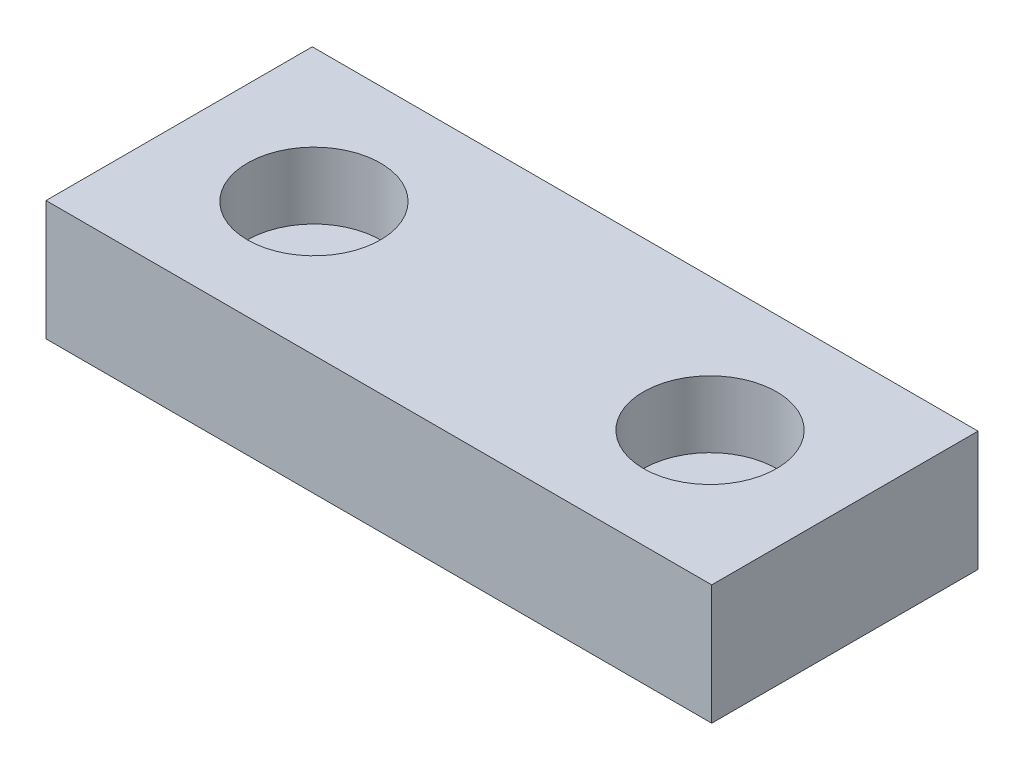
SolidWorks part; units mm, degrees
ref_plane "Front Plane" through (0, 0, 0) normal (0, 0, 1) x (1, 0, 0)
ref_plane "Top Plane" through (0, 0, 0) normal (0, 1, 0) x (1, 0, 0)
ref_plane "Right Plane" through (0, 0, 0) normal (1, 0, 0) x (0, 0, -1)
sketch "Sketch1" plane through (0, 0, 0) normal (0, 1, 0) x (1, 0, 0)
  line L1 (-50, -20) -> (50, -20)
  line L2 (-50, -20) -> (-50, 20)
  line L3 (-50, 20) -> (50, 20)
  line L4 (50, -20) -> (50, 20)
  line L5 (-50, -20) -> (50, 20) construction
  line L6 (-50, 20) -> (50, -20) construction
  point P0 (0, 0)
  dimension "D1" = 40
  dimension "D2" = 100
extrude "Boss-Extrude1" add sketch "Sketch1" along normal blind 18
sketch "Sketch3" plane through (0, 18, 0) normal (0, 1, 0) x (1, 0, 0)
  circle A0 centre (-29.75, 0) radius 10
  circle A1 centre (29.75, 0) radius 10
  dimension "D1" = 20
  dimension "D2" = 20
  dimension "D3" = 59.5
  dimension "D4" = 29.75
extrude "Cut-Extrude1" cut sketch "Sketch3" against normal blind 10
